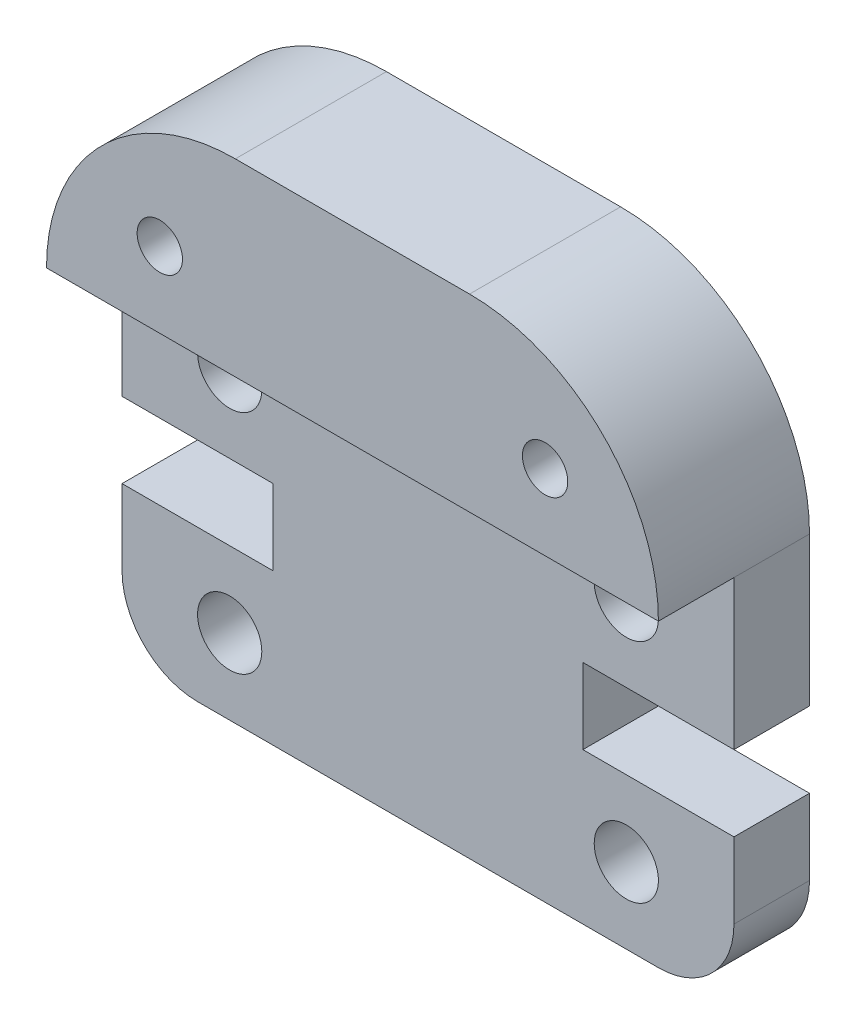
SolidWorks part; units mm, degrees
ref_plane "Front Plane" through (0, 0, 0) normal (0, 0, 1) x (1, 0, 0)
ref_plane "Top Plane" through (0, 0, 0) normal (0, 1, 0) x (1, 0, 0)
ref_plane "Right Plane" through (0, 0, 0) normal (1, 0, 0) x (0, 0, -1)
sketch "Sketch2" plane through (0, 0, 0) normal (0, 0, 1) x (1, 0, 0)
  line L0 (0, 9.945) -> (0, 6)
  line L1 (5, 14.945) -> (11.2, 14.945)
  line L2 (8.1, 14.945) -> (8.1, 0) construction
  line L3 (2, 0) -> (14.2, 0)
  line L4 (12.2, 4) -> (16.2, 4)
  line L5 (12.2, 6) -> (12.2, 4)
  line L6 (16.2, 6) -> (12.2, 6)
  line L7 (16.2, 2) -> (16.2, 4)
  line L8 (16.2, 9.945) -> (16.2, 6)
  line L17 (0, 2) -> (0, 4)
  line L18 (0, 6) -> (4, 6)
  line L20 (4, 6) -> (4, 4)
  line L21 (4, 4) -> (0, 4)
  circle A0 centre (13.35, 8) radius 0.85
  circle A1 centre (13.35, 2) radius 0.85
  arc A2 (16.2, 2) -> (14.2, 0) centre (14.2, 2) cw
  circle A3 centre (13.2, 11.942) radius 0.6
  arc A4 (11.2, 14.945) -> (16.2, 9.945) centre (11.2, 9.945) cw
  arc A11 (5, 14.945) -> (0, 9.945) centre (5, 9.945) ccw
  circle A13 centre (3, 11.942) radius 0.6
  arc A15 (0, 2) -> (2, 0) centre (2, 2) ccw
  circle A17 centre (2.85, 2) radius 0.85
  circle A18 centre (2.85, 8) radius 0.85
  dimension "D1" = 1.2
  dimension "D2" = 1.7
  dimension "D3" = 5
  dimension "D4" = 2
  dimension "D5" = 3
  dimension "D6" = 8.1
  dimension "D7" = 8
  dimension "D9" = 14.945
  dimension "D8" = 3.003
extrude "Boss-Extrude1" add sketch "Sketch2" along normal blind 4
sketch "Sketch3" plane through (0, 0, 4) normal (0, 0, -1) x (-1, 0, 0)
  line L0 (-16.2, 9.945) -> (0, 9.945)
  line L1 (0, 9.945) -> (0, 0)
  line L2 (0, 0) -> (-16.2, 0)
  line L3 (-16.2, 0) -> (-16.2, 9.945)
extrude "Cut-Extrude2" cut sketch "Sketch3" along normal blind 2
equation "\"D6@Sketch2\"= \"fingerWidth@parametersSketch@prostheticParameters.SLDPRT\" / 2'Finger width"
equation "\"D9@Sketch2\"= ( ( \"HL@parametersSketch@prostheticParameters.SLDPRT\" * 0.097 ) - 3 ) 'DIP legth-Silicone Sheet DIP"
equation "\"D1@Sketch2\"= 1 + \"tol1@parametersSketch@prostheticParameters.SLDPRT\""
equation "\"D2@Sketch2\"= 1.5 + \"tol1@parametersSketch@prostheticParameters.SLDPRT\""
